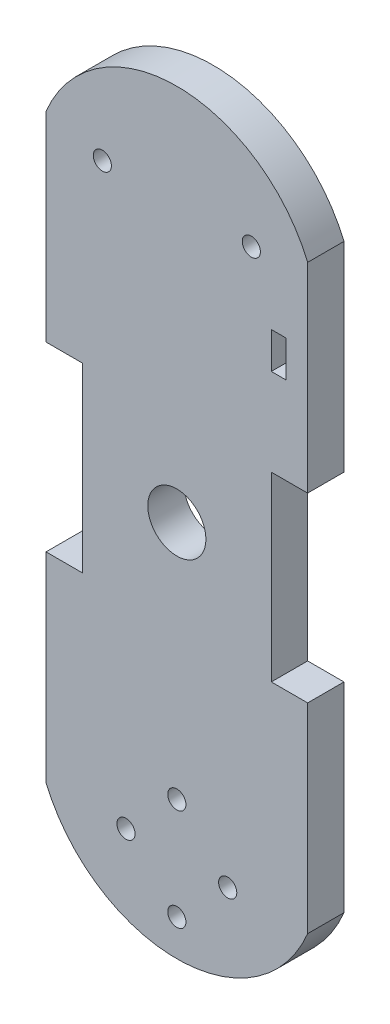
SolidWorks part; units mm, degrees
ref_plane "Front Plane" through (0, 0, 0) normal (0, 0, 1) x (1, 0, 0)
ref_plane "Top Plane" through (0, 0, 0) normal (0, 1, 0) x (1, 0, 0)
ref_plane "Right Plane" through (0, 0, 0) normal (1, 0, 0) x (0, 0, -1)
sketch "Sketch1" plane through (0, 0, 0) normal (0, 0, 1) x (1, 0, 0)
  line L0 (-3.1214, 0) -> (4.0463, 0) construction
  line L1 (0, 2.8027) -> (0, -2.1665) construction
  line L2 (-12.58, -12) -> (17.4307, -12) construction
  line L3 (-15.0311, 40) -> (21.0528, 40) construction
  line L4 (-18, 80) -> (-18, 52.5)
  line L5 (-18, 52.5) -> (-13, 52.5)
  line L6 (-13, 52.5) -> (-13, 27.5)
  line L7 (-13, 27.5) -> (-18, 27.5)
  line L8 (-18, 27.5) -> (-18, 0)
  line L9 (18, 80) -> (18, 52.5)
  line L10 (18, 52.5) -> (13, 52.5)
  line L11 (13, 52.5) -> (13, 27.5)
  line L12 (13, 27.5) -> (18, 27.5)
  line L13 (18, 27.5) -> (18, 0)
  line L15 (13, 69.5) -> (15, 69.5)
  line L16 (13, 69.5) -> (13, 64.5)
  line L17 (13, 64.5) -> (15, 64.5)
  line L18 (15, 69.5) -> (15, 64.5)
  circle A0 centre (0, 0) radius 7 construction
  circle A1 centre (0, 7) radius 1.25
  circle A2 centre (7, 0) radius 1.25
  circle A3 centre (0, -7) radius 1.25
  circle A4 centre (-7, 0) radius 1.25
  arc A5 (-18, 0) -> (18, 0) centre (0, 7.5) ccw
  circle A6 centre (0, 40) radius 4
  arc A7 (-18, 80) -> (18, 80) centre (0, 72.5) cw
  circle A8 centre (-10.25, 78) radius 1.25
  circle A9 centre (10.25, 78) radius 1.25
  point P3 (0, 7)
  point P4 (7, 0)
  point P5 (0, -7)
  point P6 (-7, 0)
  dimension "D1" = 14
  dimension "D2" = 2.5
  dimension "D7" = 8
  dimension "D8" = 2.5
  dimension "D3" = 12
  dimension "D4" = 18
  dimension "D5" = 18
  dimension "D6" = 40
  dimension "D9" = 20.5
  dimension "D10" = 10.25
  dimension "D11" = 38
  dimension "D12" = 25
  dimension "D13" = 12.5
  dimension "D14" = 5
  dimension "D15" = 5
  dimension "D16" = 25
  dimension "D17" = 12.5
  dimension "D18" = 5
  dimension "D19" = 2
  dimension "D20" = 8.5
  dimension "D21" = 3
extrude "Boss-Extrude1" add sketch "Sketch1" along normal blind 5
